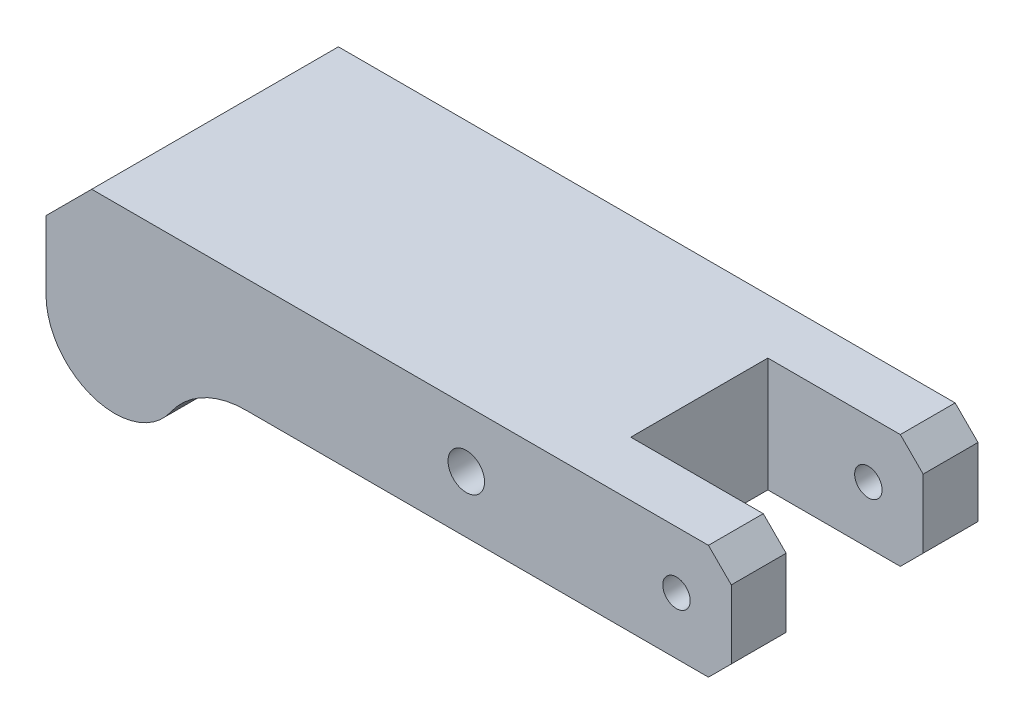
SolidWorks part; units mm, degrees
ref_plane "Front Plane" through (0, 0, 0) normal (0, 0, 1) x (1, 0, 0)
ref_plane "Top Plane" through (0, 0, 0) normal (0, 1, 0) x (1, 0, 0)
ref_plane "Right Plane" through (0, 0, 0) normal (1, 0, 0) x (0, 0, -1)
sketch "Sketch1" plane through (0, 0, 0) normal (0, 0, 1) x (1, 0, 0)
  line L0 (75, 0) -> (63, 0) construction
  line L1 (-31.2772, -12.5) -> (75, -12.5)
  line L2 (-75, -12.5) -> (-75, 12.5)
  line L3 (-75, 12.5) -> (75, 12.5)
  line L4 (75, -12.5) -> (75, 12.5)
  line L5 (-75, -12.5) -> (75, 12.5) construction
  line L6 (-75, 12.5) -> (75, -12.5) construction
  line L7 (75, 0) -> (17, 0) construction
  arc A0 (-75, -12.5) -> (-47.6902, -21.0714) centre (-60, -12.5) ccw
  arc A1 (-31.2772, -12.5) -> (-47.6902, -21.0714) centre (-31.2772, -32.5) ccw
  circle A2 centre (63, 0) radius 3
  circle A3 centre (17, 0) radius 4
  point P0 (0, 0)
  dimension "D3" = 15
  dimension "D4" = 20
  dimension "D6" = 6
  dimension "D7" = 8
  dimension "D1" = 150
  dimension "D2" = 25
  dimension "D5" = 12
  dimension "D8" = 58
extrude "Boss-Extrude1" add sketch "Sketch1" along normal blind 54
sketch "Sketch2" plane through (0, 12.5, 0) normal (0, 1, 0) x (1, 0, 0)
  line L0 (75, -54) -> (75, 0) construction
  line L1 (75, -54) -> (75, 0)
  line L2 (75, 0) -> (-75, 0) construction
  line L3 (41, -42) -> (75, -42)
  line L4 (41, -42) -> (41, -12)
  line L5 (41, -12) -> (75, -12)
  line L7 (41, -42) -> (75, -27) construction
  line L8 (41, -12) -> (75, -27) construction
  point P2 (75, -27)
  dimension "D1" = 34
  dimension "D2" = 30
  dimension "D3" = 12
extrude "Cut-Extrude1" cut sketch "Sketch2" against normal through all contours L5 L4 L3 L1
chamfer "Chamfer1" distance 10 angle 45 1 edges at (-75, 12.5, 27)
chamfer "Chamfer2" distance 5 angle 45 4 edges at (75, -12.5, 6) (75, -12.5, 48) (75, 12.5, 6) (75, 12.5, 48)
